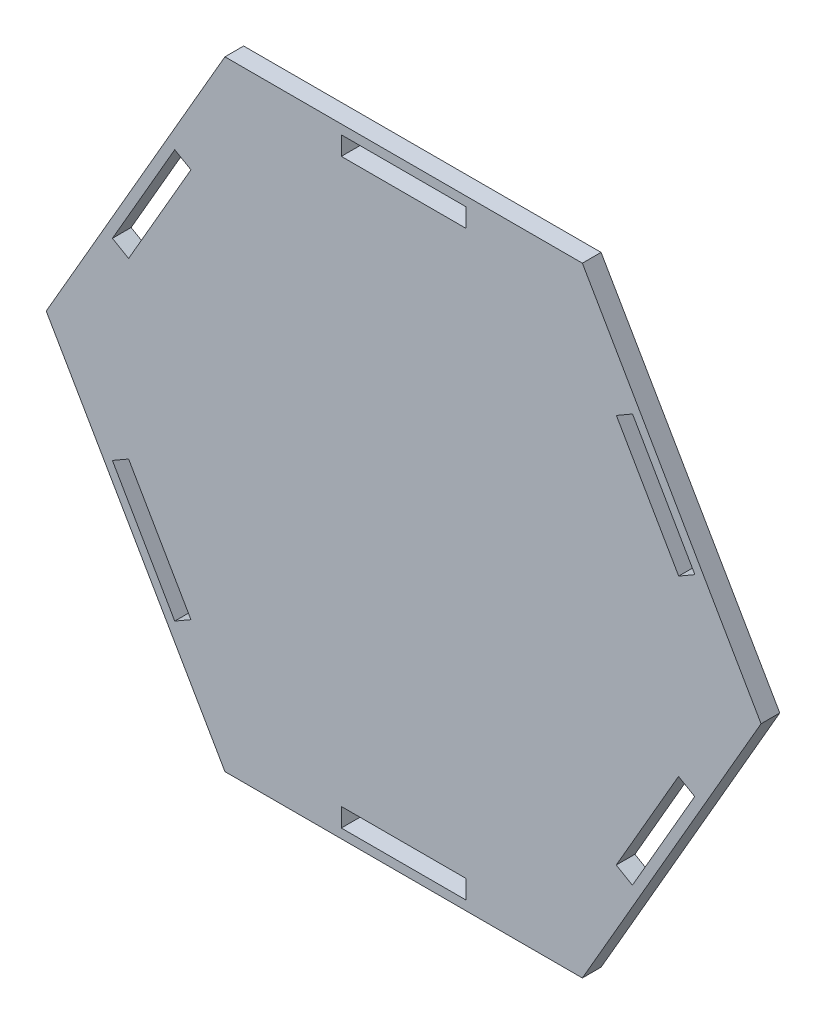
SolidWorks part; units mm, degrees
ref_plane "Front Plane" through (0, 0, 0) normal (0, 0, 1) x (1, 0, 0)
ref_plane "Top Plane" through (0, 0, 0) normal (0, 1, 0) x (1, 0, 0)
ref_plane "Right Plane" through (0, 0, 0) normal (1, 0, 0) x (0, 0, -1)
sketch "Model" plane through (0, 0, 0) normal (0, 0, 1) x (1, 0, 0)
  line L0 (82.1133, 103.8592) -> (82.1133, 100.8592)
  line L1 (82.1133, 100.8592) -> (102.1133, 100.8592)
  line L2 (102.1133, 100.8592) -> (102.1133, 103.8592)
  line L3 (102.1133, 103.8592) -> (82.1133, 103.8592)
  line L4 (82.1133, 10.5368) -> (82.1133, 7.5368)
  line L5 (82.1133, 7.5368) -> (102.1133, 7.5368)
  line L6 (102.1133, 7.5368) -> (102.1133, 10.5368)
  line L7 (102.1133, 10.5368) -> (82.1133, 10.5368)
  line L8 (126.2156, 24.4424) -> (128.8137, 22.9424)
  line L9 (128.8137, 22.9424) -> (138.8137, 40.2629)
  line L10 (138.8137, 40.2629) -> (136.2156, 41.7629)
  line L11 (136.2156, 41.7629) -> (126.2156, 24.4424)
  line L12 (128.8391, 88.4291) -> (126.2411, 86.9291)
  line L13 (126.2411, 86.9291) -> (136.2411, 69.6085)
  line L14 (136.2411, 69.6085) -> (138.8391, 71.1085)
  line L15 (138.8391, 71.1085) -> (128.8391, 88.4291)
  line L16 (55.3875, 22.9277) -> (57.9856, 24.4277)
  line L17 (57.9856, 24.4277) -> (47.9856, 41.7482)
  line L18 (47.9856, 41.7482) -> (45.3875, 40.2482)
  line L19 (45.3875, 40.2482) -> (55.3875, 22.9277)
  line L20 (45.3875, 71.1085) -> (47.9856, 69.6085)
  line L21 (47.9856, 69.6085) -> (57.9856, 86.9291)
  line L22 (57.9856, 86.9291) -> (55.3875, 88.4291)
  line L23 (55.3875, 88.4291) -> (45.3875, 71.1085)
  line L24 (149.4572, 55.698) -> (120.7853, 105.3592)
  line L25 (120.7853, 105.3592) -> (63.4414, 105.3592)
  line L26 (63.4414, 105.3592) -> (34.7695, 55.698)
  line L27 (34.7695, 55.698) -> (63.4414, 6.0368)
  line L28 (63.4414, 6.0368) -> (120.7853, 6.0368)
  line L29 (120.7853, 6.0368) -> (149.4572, 55.698)
extrude "Boss-Extrude1" add sketch "Model" along normal blind 3
